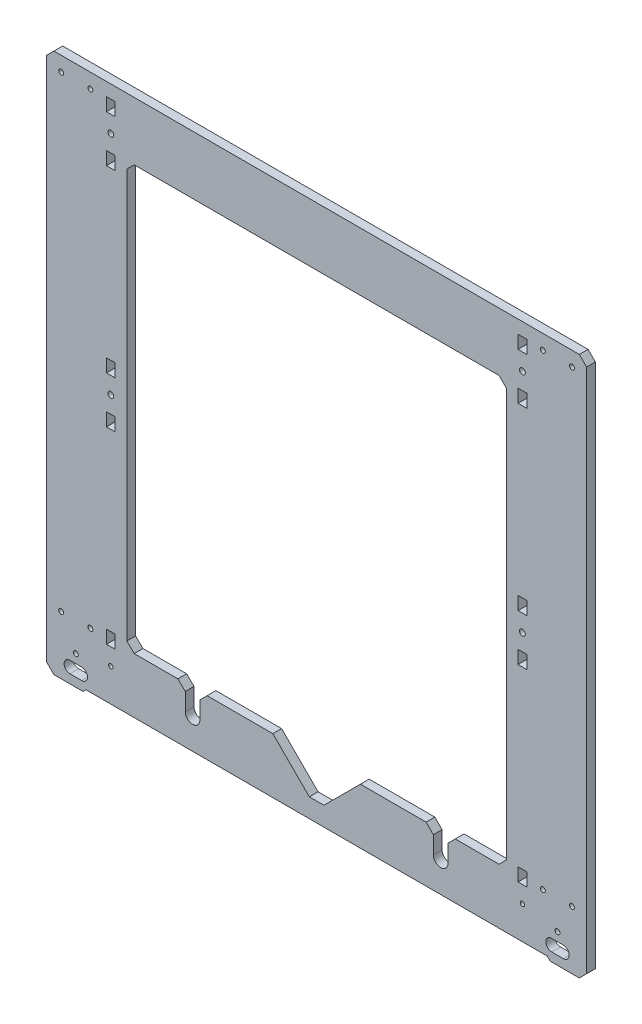
SolidWorks part; units mm, degrees
material "Sosna"
ref_plane "Płaszczyzna przednia" through (0, 0, 0) normal (0, 0, 1) x (1, 0, 0)
ref_plane "Płaszczyzna górna" through (0, 0, 0) normal (0, 1, 0) x (1, 0, 0)
ref_plane "Płaszczyzna prawa" through (0, 0, 0) normal (1, 0, 0) x (0, 0, -1)
sketch "Szkic1" plane through (0, 0, 0) normal (0, 0, 1) x (1, 0, 0)
  line L1 (-185, -185) -> (185, -185)
  line L2 (-185, -185) -> (-185, 185)
  line L3 (-185, 185) -> (185, 185)
  line L4 (185, -185) -> (185, 185)
  line L5 (0, 185) -> (0, -185) construction
  line L6 (-185, 0) -> (185, 0) construction
  line L7 (-130, 145) -> (130, 145)
  line L8 (-130, 145) -> (-130, -145)
  line L9 (-130, -145) -> (130, -145)
  line L10 (130, 145) -> (130, -145)
  point P0 (0, 0)
  dimension "D1" = 370
  dimension "D2" = 370
  dimension "D3" = 40
  dimension "D4" = 55
  dimension "D5" = 55
  dimension "D6" = 40
extrude "Dodanie-wyciągnięcie1" add sketch "Szkic1" along normal blind 6
sketch "Szkic2" plane through (0, 0, 6) normal (0, 0, 1) x (1, 0, 0)
  line L0 (0, 0) -> (0, -185) construction
  line L1 (-185, -185) -> (185, -185) construction
  line L2 (90, -145) -> (90, -162)
  line L3 (-130, -145) -> (130, -145) construction
  line L4 (90, -162) -> (80, -162) construction
  line L5 (80, -162) -> (80, -145)
  line L6 (85, -162) -> (85, -145) construction
  line L7 (130, -145) -> (130, 145) construction
  line L8 (80, -145) -> (90, -145)
  line L9 (-5, -170) -> (5, -170)
  line L10 (5, -170) -> (30, -145)
  line L11 (30, -145) -> (-30, -145)
  line L12 (-90, -145) -> (-90, -162)
  line L13 (-80, -145) -> (-90, -145)
  line L14 (-80, -162) -> (-80, -145)
  line L15 (-5, -170) -> (-30, -145)
  arc A0 (80, -162) -> (90, -162) centre (85, -162) ccw
  arc A1 (-80, -162) -> (-90, -162) centre (-85, -162) cw
  point P16 (85, -167)
  point P27 (0, -145)
  point P28 (0, -170)
  dimension "D3" = 18
  dimension "D1" = 10
  dimension "D2" = 45
  dimension "D4" = 15
  dimension "D5" = 10
  dimension "D6" = 60
extrude "Wytnij-wyciągnięcie1" cut sketch "Szkic2" against normal up to next
chamfer "Sfazowanie1" distance 5 angle 45 12 edges at (90, -145, 3) (80, -145, 3) (-90, -145, 3) (-80, -145, 3) (-185, 185, 3) (185, 185, 3) (185, -185, 3) (-185, -185, 3) (130, 145, 3) (-130, 145, 3) (-130, -145, 3) (130, -145, 3)
sketch "Szkic3" plane through (0, 0, 6) normal (0, 0, 1) x (1, 0, 0)
  line L0 (0, 0) -> (0, -185) construction
  line L1 (-180, -185) -> (180, -185) construction
  line L2 (-158, -183) -> (158, -183)
  line L3 (158, -183) -> (160, -185)
  line L4 (160, -185) -> (-160, -185)
  line L5 (-158, -183) -> (-160, -185)
  point P11 (0, -183)
  dimension "D1" = 45
  dimension "D2" = 2
  dimension "D3" = 20
extrude "Wytnij-wyciągnięcie2" cut sketch "Szkic3" against normal up to next
sketch "Szkic4" plane through (0, 0, 6) normal (0, 0, 1) x (1, 0, 0)
  line L0 (180, 185) -> (-180, 185) construction
  line L1 (138, 176) -> (144, 176)
  line L2 (138, 176) -> (138, 167)
  line L3 (138, 167) -> (144, 167)
  line L4 (144, 176) -> (144, 167)
  line L5 (138, 144) -> (144, 144)
  line L6 (138, 144) -> (138, 135)
  line L7 (138, 135) -> (144, 135)
  line L8 (144, 144) -> (144, 135)
  line L9 (130, -140) -> (130, 140) construction
  line L10 (141, 167) -> (141, 144) construction
  line L11 (0, 0) -> (0, 185) construction
  line L12 (138, -11) -> (138, -20)
  line L13 (138, -11) -> (144, -11)
  line L14 (144, -11) -> (144, -20)
  line L15 (138, -20) -> (144, -20)
  line L16 (138, 21) -> (138, 12)
  line L17 (138, 21) -> (144, 21)
  line L18 (144, 21) -> (144, 12)
  line L19 (138, 12) -> (144, 12)
  line L28 (141, -160.5) -> (141, -149) construction
  line L29 (138, -140) -> (144, -140)
  line L30 (138, -140) -> (138, -149)
  line L31 (138, -149) -> (144, -149)
  line L32 (144, -140) -> (144, -149)
  line L34 (160, -185) -> (180, -185) construction
  circle A1 centre (141, 155.5) radius 2
  circle A2 centre (141, 0.5) radius 2
  circle A4 centre (141, -160.5) radius 1.5
  dimension "D6" = 4
  dimension "D10" = 11.5
  dimension "D11" = 3
  dimension "D1" = 9
  dimension "D2" = 41
  dimension "D3" = 8
  dimension "D4" = 6
  dimension "D5" = 9
  dimension "D7" = 2
  dimension "D8" = 155
  dimension "D9" = 45
extrude "Wytnij-wyciągnięcie3" cut sketch "Szkic4" against normal up to next
sketch "Szkic5" plane through (0, 0, 6) normal (0, 0, 1) x (1, 0, 0)
  line L0 (185, -180) -> (185, 180) construction
  line L1 (180, 185) -> (-180, 185) construction
  line L2 (175, 175) -> (175, -145) construction
  line L3 (175, -145) -> (155, -145) construction
  line L4 (160, -185) -> (180, -185) construction
  line L5 (165, -145) -> (165, -165) construction
  circle A0 centre (175, 175) radius 1.7
  circle A1 centre (155, 175) radius 1.7
  circle A2 centre (175, -145) radius 1.7
  circle A3 centre (155, -145) radius 1.7
  circle A4 centre (165, -165) radius 1.7
  dimension "D6" = 40
  dimension "D5" = 3.4
  dimension "D1" = 10
  dimension "D2" = 10
  dimension "D3" = 10
  dimension "D4" = 20
  dimension "D7" = 20
extrude "Wytnij-wyciągnięcie4" cut sketch "Szkic5" against normal up to next
sketch "Szkic6" plane through (0, 0, 0) normal (0, 0, -1) x (-1, 0, 0)
  line L0 (161, -175) -> (169, -175) construction
  line L1 (161, -171) -> (169, -171)
  line L2 (161, -179) -> (169, -179)
  line L3 (185, 180) -> (185, -180) construction
  line L4 (180, -185) -> (160, -185) construction
  arc A0 (161, -171) -> (161, -179) centre (161, -175) ccw
  arc A1 (169, -179) -> (169, -171) centre (169, -175) ccw
  point P2 (165, -175)
  point P7 (173, -175)
  point P12 (157, -175)
  dimension "D1" = 12
  dimension "D2" = 6
  dimension "D3" = 16
  dimension "D4" = 8
extrude "Wytnij-wyciągnięcie5" cut sketch "Szkic6" against normal up to next
mirror "Lustro1" about plane through (0, 0, 0) normal (1, 0, 0) of "Wytnij-wyciągnięcie4", "Wytnij-wyciągnięcie5", "Wytnij-wyciągnięcie3"
equation "\"D5@Szkic1\"=\"D4@Szkic1\""
equation "\"D6@Szkic1\"=\"D3@Szkic1\""
equation "\"D3@Szkic5\"=\"D2@Szkic5\""
